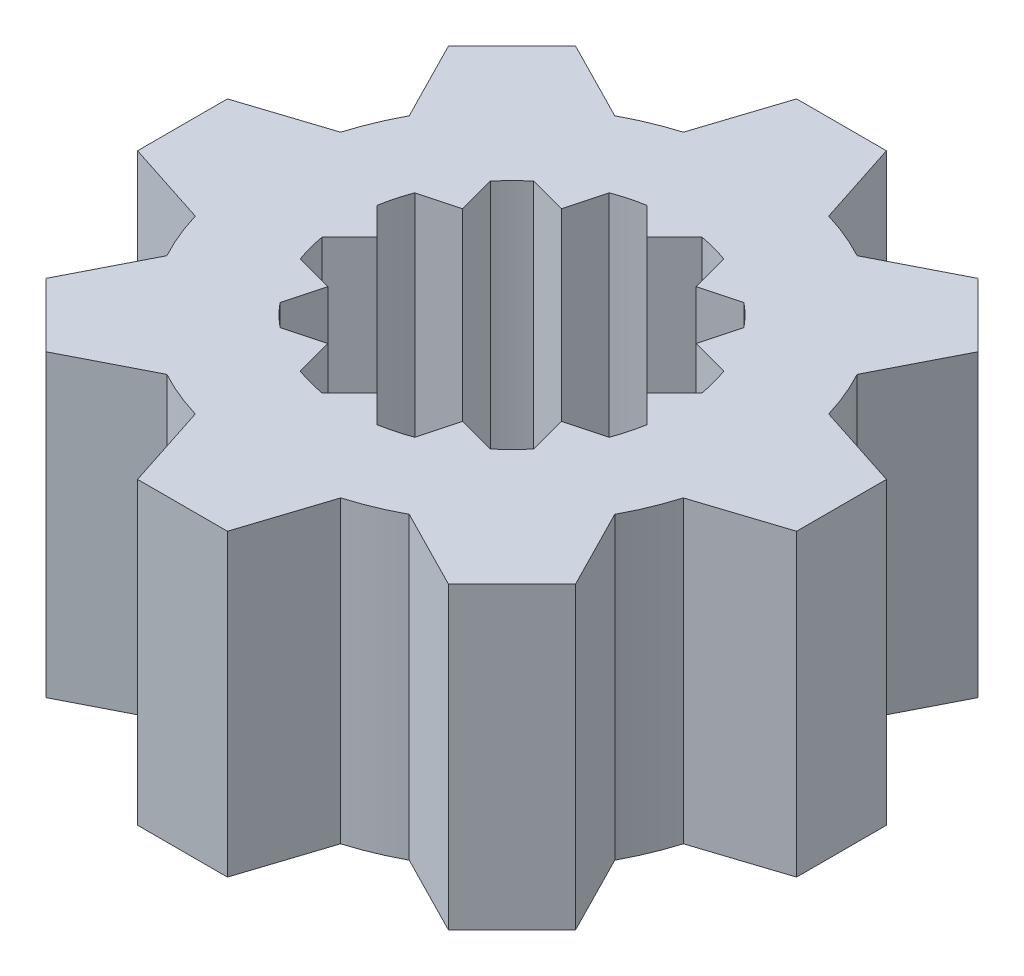
SolidWorks part; units mm, degrees
ref_plane "Front Plane" through (0, 0, 0) normal (0, 0, 1) x (1, 0, 0)
ref_plane "Top Plane" through (0, 0, 0) normal (0, 1, 0) x (1, 0, 0)
ref_plane "Right Plane" through (0, 0, 0) normal (1, 0, 0) x (0, 0, -1)
sketch "Sketch1" plane through (0, 0, 0) normal (0, 1, 0) x (1, 0, 0)
  line L0 (0, 5.5) -> (0, 4.5) construction
  line L1 (2.75, 4.7631) -> (2.25, 3.8971) construction
  line L2 (4.7631, 2.75) -> (3.8971, 2.25) construction
  line L3 (5.5, 0) -> (4.5, 0) construction
  line L4 (4.7631, -2.75) -> (3.8971, -2.25) construction
  line L5 (2.75, -4.7631) -> (2.25, -3.8971) construction
  line L6 (0, -5.5) -> (0, -4.5) construction
  line L7 (-2.75, -4.7631) -> (-2.25, -3.8971) construction
  line L8 (-4.7631, -2.75) -> (-3.8971, -2.25) construction
  line L9 (-5.5, 0) -> (-4.5, 0) construction
  line L10 (-4.7631, 2.75) -> (-3.8971, 2.25) construction
  line L11 (-2.75, 4.7631) -> (-2.25, 3.8971) construction
  line L12 (0, 4.5) -> (1, 5.5) construction
  line L13 (1, 5.5) -> (-1, 5.5) construction
  line L14 (-1, 5.5) -> (0, 4.5) construction
  line L15 (0, 4.5) -> (-0.9221, 5.4221)
  line L16 (0, 4.5) -> (0.9221, 5.4221)
  line L17 (2.25, 3.8971) -> (3.5097, 4.2346)
  line L18 (2.25, 3.8971) -> (1.9125, 5.1568)
  line L19 (3.8971, 2.25) -> (5.1568, 1.9125)
  line L20 (3.8971, 2.25) -> (4.2346, 3.5097)
  line L21 (4.5, 0) -> (5.4221, -0.9221)
  line L22 (4.5, 0) -> (5.4221, 0.9221)
  line L23 (3.8971, -2.25) -> (4.2346, -3.5097)
  line L24 (3.8971, -2.25) -> (5.1568, -1.9125)
  line L25 (2.25, -3.8971) -> (1.9125, -5.1568)
  line L26 (2.25, -3.8971) -> (3.5097, -4.2346)
  line L27 (0, -4.5) -> (-0.9221, -5.4221)
  line L28 (0, -4.5) -> (0.9221, -5.4221)
  line L29 (-2.25, -3.8971) -> (-3.5097, -4.2346)
  line L30 (-2.25, -3.8971) -> (-1.9125, -5.1568)
  line L31 (-3.8971, -2.25) -> (-5.1568, -1.9125)
  line L32 (-3.8971, -2.25) -> (-4.2346, -3.5097)
  line L33 (-4.5, 0) -> (-5.4221, 0.9221)
  line L34 (-4.5, 0) -> (-5.4221, -0.9221)
  line L35 (-3.8971, 2.25) -> (-4.2346, 3.5097)
  line L36 (-3.8971, 2.25) -> (-5.1568, 1.9125)
  line L37 (-2.25, 3.8971) -> (-1.9125, 5.1568)
  line L38 (-2.25, 3.8971) -> (-3.5097, 4.2346)
  line L39 (0, 8.5) -> (0, 11) construction
  line L40 (-1.5, 11) -> (1.5, 11)
  line L41 (-1.5, 11) -> (-2.4259, 8.1465)
  line L42 (1.5, 11) -> (2.4259, 8.1465)
  line L43 (6.7175, 8.8388) -> (4.045, 7.4758)
  line L44 (6.7175, 8.8388) -> (8.8388, 6.7175)
  line L45 (8.8388, 6.7175) -> (7.4758, 4.045)
  line L46 (11, 1.5) -> (8.1465, 2.4259)
  line L47 (11, 1.5) -> (11, -1.5)
  line L48 (11, -1.5) -> (8.1465, -2.4259)
  line L49 (8.8388, -6.7175) -> (7.4758, -4.045)
  line L50 (8.8388, -6.7175) -> (6.7175, -8.8388)
  line L51 (6.7175, -8.8388) -> (4.045, -7.4758)
  line L52 (1.5, -11) -> (2.4259, -8.1465)
  line L53 (1.5, -11) -> (-1.5, -11)
  line L54 (-1.5, -11) -> (-2.4259, -8.1465)
  line L55 (-6.7175, -8.8388) -> (-4.045, -7.4758)
  line L56 (-6.7175, -8.8388) -> (-8.8388, -6.7175)
  line L57 (-8.8388, -6.7175) -> (-7.4758, -4.045)
  line L58 (-11, -1.5) -> (-8.1465, -2.4259)
  line L59 (-11, -1.5) -> (-11, 1.5)
  line L60 (-11, 1.5) -> (-8.1465, 2.4259)
  line L61 (-8.8388, 6.7175) -> (-7.4758, 4.045)
  line L62 (-8.8388, 6.7175) -> (-6.7175, 8.8388)
  line L63 (-6.7175, 8.8388) -> (-4.045, 7.4758)
  circle A0 centre (0, 0) radius 2.75 construction
  circle A1 centre (0, 0) radius 5.5 construction
  arc A2 (0.9221, 5.4221) -> (1.9125, 5.1568) centre (0, 0) cw
  arc A3 (3.5097, 4.2346) -> (4.2346, 3.5097) centre (0, 0) cw
  arc A4 (5.4221, 0.9221) -> (5.1568, 1.9125) centre (0, 0) ccw
  arc A5 (5.1568, -1.9125) -> (5.4221, -0.9221) centre (0, 0) ccw
  arc A6 (3.5097, -4.2346) -> (4.2346, -3.5097) centre (0, 0) ccw
  arc A7 (0.9221, -5.4221) -> (1.9125, -5.1568) centre (0, 0) ccw
  arc A8 (-1.9125, -5.1568) -> (-0.9221, -5.4221) centre (0, 0) ccw
  arc A9 (-3.5097, -4.2346) -> (-4.2346, -3.5097) centre (0, 0) cw
  arc A10 (-5.1568, -1.9125) -> (-5.4221, -0.9221) centre (0, 0) cw
  arc A11 (-5.4221, 0.9221) -> (-5.1568, 1.9125) centre (0, 0) cw
  arc A12 (-4.2346, 3.5097) -> (-3.5097, 4.2346) centre (0, 0) cw
  arc A13 (-0.9221, 5.4221) -> (-1.9125, 5.1568) centre (0, 0) ccw
  circle A14 centre (0, 0) radius 8.5 construction
  arc A15 (2.4259, 8.1465) -> (4.045, 7.4758) centre (0, 0) cw
  arc A16 (7.4758, 4.045) -> (8.1465, 2.4259) centre (0, 0) cw
  arc A17 (8.1465, -2.4259) -> (7.4758, -4.045) centre (0, 0) cw
  arc A18 (4.045, -7.4758) -> (2.4259, -8.1465) centre (0, 0) cw
  arc A19 (-2.4259, -8.1465) -> (-4.045, -7.4758) centre (0, 0) cw
  arc A20 (-7.4758, -4.045) -> (-8.1465, -2.4259) centre (0, 0) cw
  arc A21 (-8.1465, 2.4259) -> (-7.4758, 4.045) centre (0, 0) cw
  arc A22 (-4.045, 7.4758) -> (-2.4259, 8.1465) centre (0, 0) cw
  point P31 (0, 0)
  point P71 (0, 11)
  point P105 (0, 0)
  dimension "D1" = 5.5
  dimension "D2" = 11
  dimension "D5" = 17
  dimension "D4" = 1
  dimension "D6" = 2.5
  dimension "D7" = 3
  dimension "D8" = 3
  dimension "D3" = 12
  dimension "D9" = 8
extrude "Boss-Extrude1" add sketch "Sketch1" along normal blind 10
